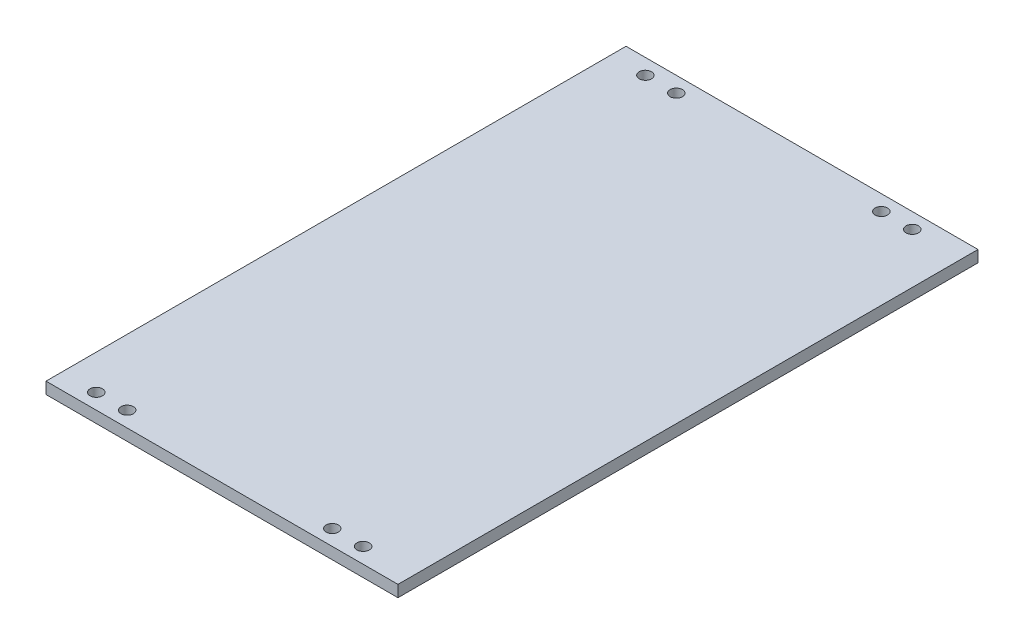
SolidWorks part; units mm, degrees
ref_plane "前视基准面" through (0, 0, 0) normal (0, 0, 1) x (1, 0, 0)
ref_plane "上视基准面" through (0, 0, 0) normal (0, 1, 0) x (1, 0, 0)
ref_plane "右视基准面" through (0, 0, 0) normal (1, 0, 0) x (0, 0, -1)
other "Configuration Table"
sketch "草图1" plane through (0, 2.2592, 0) normal (0, -1, 0) x (1, 0, 0)
  line L0 (65.205, -47.1117) -> (-25.8155, -47.1117)
  line L1 (65.205, -47.1117) -> (65.205, 102.8883)
  line L2 (-25.8155, -47.1117) -> (-25.8155, 102.8883)
  line L3 (65.205, 102.8883) -> (-25.8155, 102.8883)
  line L4 (77.0433, 27.8883) -> (-39.2006, 27.8883) construction
  circle A0 centre (44.205, -43.1117) radius 1.6
  circle A1 centre (52.205, -43.1117) radius 1.6
  circle A2 centre (52.205, 98.8883) radius 1.6
  circle A3 centre (44.205, 98.8883) radius 1.6
  circle A4 centre (-16.8155, -43.1117) radius 1.6
  circle A5 centre (-8.8155, -43.1117) radius 1.6
  circle A6 centre (-8.8155, 98.8883) radius 1.6
  circle A7 centre (-16.8155, 98.8883) radius 1.6
  dimension "D2" = 3.2
  dimension "D3" = 3.2
  dimension "D5" = 3.2
  dimension "D6" = 3.2
  dimension "D1" = 150
  dimension "D4" = 75
extrude "凸台-拉伸1" add sketch "草图1" against normal blind 3
ref_plane "机体镜像面" through (0, 0, 27.8883) normal (0, 0, 1) x (1, 0, 0)
